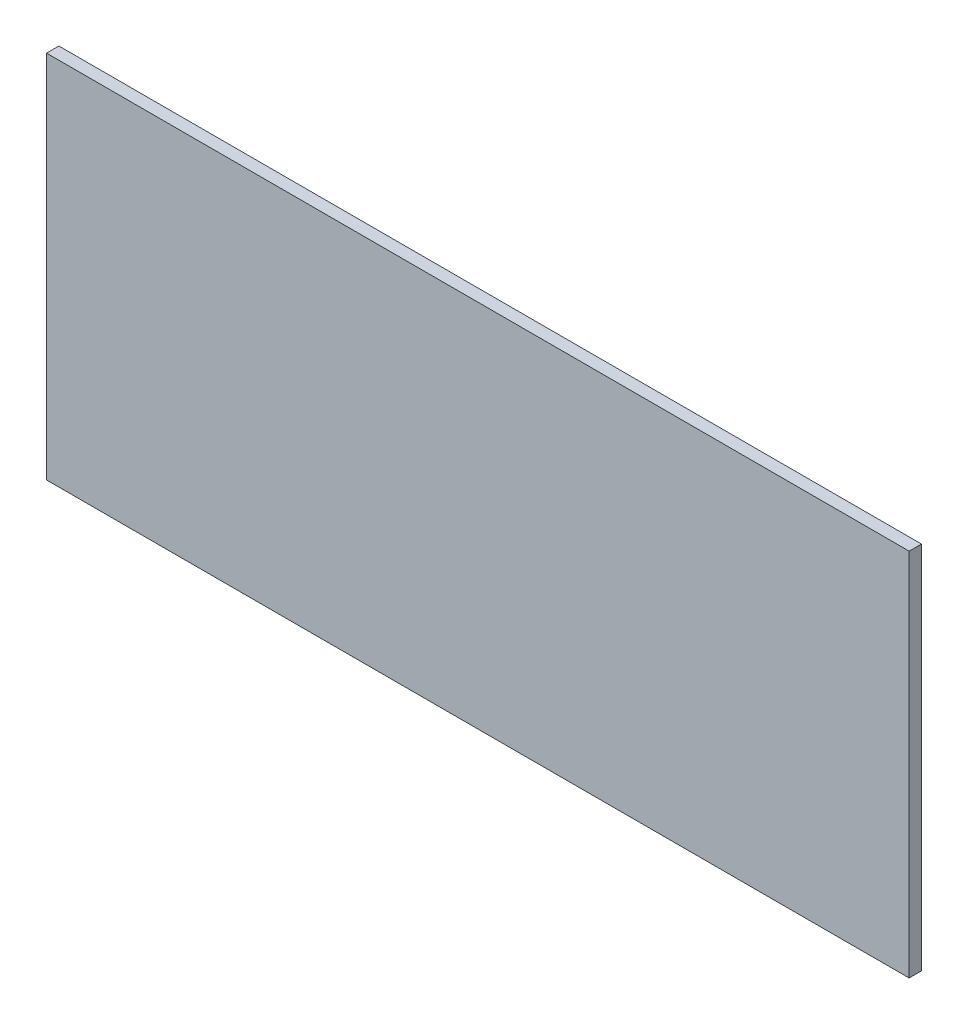
SolidWorks part; units mm, degrees
ref_plane "Front Plane" through (0, 0, 0) normal (0, 0, 1) x (1, 0, 0)
ref_plane "Top Plane" through (0, 0, 0) normal (0, 1, 0) x (1, 0, 0)
ref_plane "Right Plane" through (0, 0, 0) normal (1, 0, 0) x (0, 0, -1)
sketch "Sketch1" plane through (0, 0, 0) normal (0, 0, 1) x (1, 0, 0)
  line L1 (-89.1029, 11.4122) -> (88.6971, 11.4122)
  line L2 (-89.1029, 11.4122) -> (-89.1029, -64.7878)
  line L3 (-89.1029, -64.7878) -> (88.6971, -64.7878)
  line L4 (88.6971, 11.4122) -> (88.6971, -64.7878)
extrude "Boss-Extrude1" add sketch "Sketch1" against normal blind 2.54
